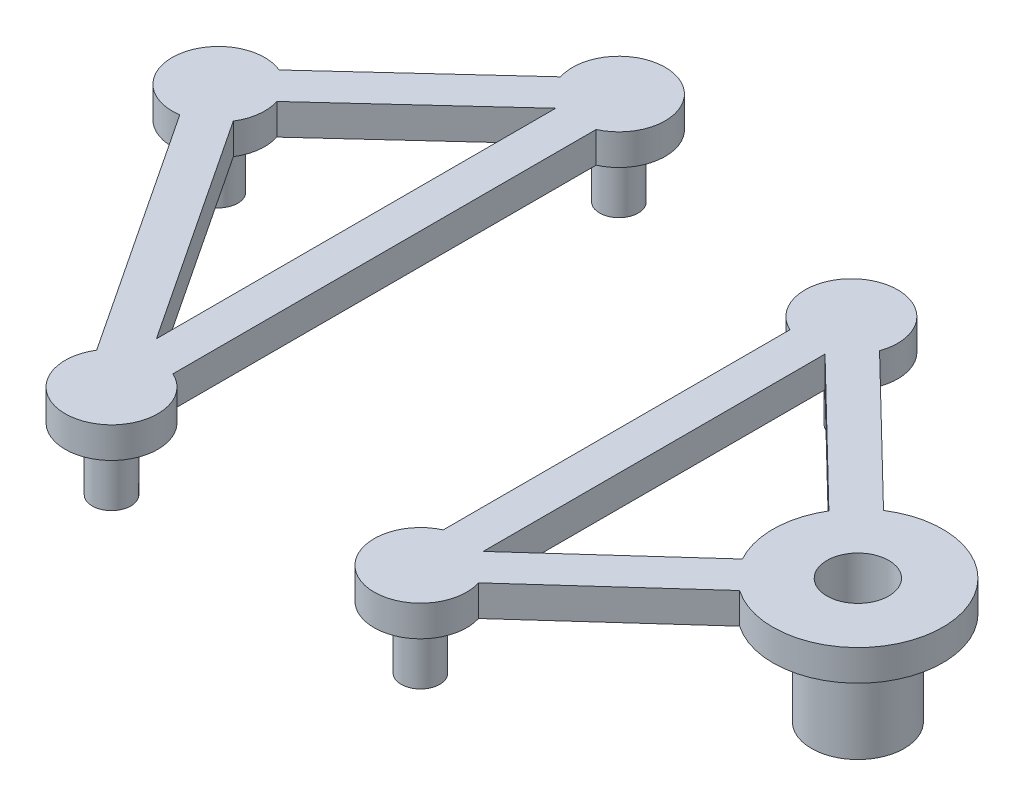
SolidWorks part; units mm, degrees
ref_plane "Спереди" through (0, 0, 0) normal (0, 0, 1) x (1, 0, 0)
ref_plane "Сверху" through (0, 0, 0) normal (0, 1, 0) x (1, 0, 0)
ref_plane "Справа" through (0, 0, 0) normal (1, 0, 0) x (0, 0, -1)
other "Configuration Table"
sketch "Эскиз1" plane through (0, 0, 0) normal (0, 1, 0) x (1, 0, 0)
  line L0 (-67.0272, 40.8721) -> (-40, 0) construction
  line L1 (-40, 0) -> (-40, 65.7) construction
  line L2 (-40, 65.7) -> (-67.0272, 40.8721) construction
  line L3 (0, 55.8) -> (29.7602, 26.8763) construction
  line L4 (29.7602, 26.8763) -> (0, 0) construction
  line L5 (0, 55.8) -> (0, 0) construction
  line L6 (0, 0) -> (-40, 0) construction
  line L8 (-66.0981, 34.9348) -> (-43.8076, 1.2257) construction
  line L11 (-48.2821, 17.0572) -> (-25.9916, -16.6519) construction
  line L12 (-37.5, 40.8721) -> (-37.5, 25.5534) construction
  line L14 (-42.5, 45.1596) -> (-42.5, 29.8408) construction
  line L15 (-58.9446, 51.6917) -> (-52.0529, 58.0226) construction
  line L17 (-54.6234, 48.8719) -> (-47.7317, 55.2027) construction
  line L18 (-64.7017, 46.4032) -> (-45.708, 63.8512)
  line L20 (-37.5, 60.2456) -> (-37.5, 5.4544)
  line L22 (-66.104, 34.9436) -> (-45.0938, 3.1707)
  line L32 (-61.3191, 42.721) -> (-42.5, 60.0087)
  line L33 (-42.5, 60.0087) -> (-42.5, 8.3131)
  line L34 (-42.5, 8.3131) -> (-61.9334, 37.7015)
  line L36 (-2.5, 38.1926) -> (-2.5, 20.958) construction
  line L38 (2.5, 19.403) -> (2.5, 2.1683) construction
  line L39 (9.5911, 49.9647) -> (19.4126, 40.4193) construction
  line L41 (9.1257, 43.4447) -> (18.1439, 34.68) construction
  line L43 (9.8251, 12.2416) -> (16.8272, 18.5652) construction
  line L45 (11.5829, 7.0919) -> (19.8959, 14.5993) construction
  line L46 (20.1346, 21.5521) -> (2.5, 5.6263)
  line L53 (2.5, 5.6263) -> (2.5, 49.8841)
  line L55 (2.5, 49.8841) -> (20.336, 32.5494)
  line L57 (-2.5, 50.3456) -> (-2.5, 5.4544)
  line L58 (5.7235, 1.8003) -> (23.4858, 17.8413)
  line L59 (5.6538, 53.7913) -> (23.8208, 36.135)
  circle A14 centre (-40, 65.7) radius 6 construction
  circle A15 centre (-67.0272, 40.8721) radius 6 construction
  circle A16 centre (-40, 0) radius 6 construction
  circle A17 centre (0, 0) radius 6 construction
  circle A18 centre (29.7602, 26.8763) radius 11 construction
  circle A19 centre (0, 55.8) radius 6 construction
  arc A20 (-66.104, 34.9436) -> (-64.7017, 46.4032) centre (-67.0272, 40.8721) cw
  arc A21 (-45.708, 63.8512) -> (-37.5, 60.2456) centre (-40, 65.7) cw
  arc A22 (-45.0938, 3.1707) -> (-37.5, 5.4544) centre (-40, 0) ccw
  arc A23 (-61.3191, 42.721) -> (-61.9334, 37.7015) centre (-67.0272, 40.8721) cw
  arc A24 (5.6538, 53.7913) -> (-2.5, 50.3456) centre (0, 55.8) ccw
  arc A25 (23.4858, 17.8413) -> (23.8208, 36.135) centre (29.7602, 26.8763) ccw
  arc A26 (-2.5, 5.4544) -> (5.7235, 1.8003) centre (0, 0) ccw
  arc A27 (20.336, 32.5494) -> (20.1346, 21.5521) centre (29.7602, 26.8763) ccw
  dimension "D14" = 12
  dimension "D15" = 12
  dimension "D16" = 12
  dimension "D17" = 12
  dimension "D18" = 12
  dimension "D19" = 22
  dimension "D1" = 55.8
  dimension "D2" = 40.1
  dimension "D3" = 41.5
  dimension "D4" = 65.7
  dimension "D5" = 49
  dimension "D6" = 36.7
  dimension "D7" = 40
  dimension "D8" = 2.5
  dimension "D9" = 2.5
  dimension "D10" = 2.5
  dimension "D11" = 2.5
  dimension "D12" = 2.5
  dimension "D13" = 2.5
  dimension "D20" = 2.5
  dimension "D21" = 2.5
  dimension "D22" = 2.5
  dimension "D23" = 2.5
  dimension "D24" = 2.5
  dimension "D25" = 2.5
extrude "Бобышка-Вытянуть1" add sketch "Эскиз1" along normal blind 4
sketch "Эскиз2" plane through (0, 0, 0) normal (0, -1, 0) x (1, 0, 0)
  circle A1 centre (-40, 0) radius 2.5
  circle A3 centre (-40, -65.7) radius 2.5
  circle A5 centre (-67.0272, -40.8721) radius 2.5
  dimension "D1" = 5
  dimension "D2" = 5
  dimension "D3" = 5
extrude "Бобышка-Вытянуть2" add sketch "Эскиз2" along normal blind 8.1
sketch "Эскиз3" plane through (0, 0, 0) normal (0, -1, 0) x (1, 0, 0)
  circle A0 centre (0, 0) radius 2.5
  circle A1 centre (0, -55.8) radius 2.5
  dimension "D1" = 5
  dimension "D2" = 5
extrude "Бобышка-Вытянуть3" add sketch "Эскиз3" along normal blind 8.1
sketch "Эскиз4" plane through (0, 0, 0) normal (0, -1, 0) x (1, 0, 0)
  circle A0 centre (29.7602, -26.8763) radius 6
  dimension "D1" = 12
extrude "Бобышка-Вытянуть4" add sketch "Эскиз4" along normal blind 12.1
sketch "Эскиз5" plane through (0, 4, 0) normal (0, 1, 0) x (1, 0, 0)
  circle A0 centre (29.7602, 26.8763) radius 4
  dimension "D1" = 8
extrude "Вырез-Вытянуть1" cut sketch "Эскиз5" against normal through all
equation "\"A\"= 12мм"
equation "\"B\"= 22мм"
equation "\"w\"= 5мм"
equation "\"D8@Эскиз1\"=\"w\"/2"
equation "\"D9@Эскиз1\"=\"w\"/2"
equation "\"D10@Эскиз1\"=\"w\"/2"
equation "\"D11@Эскиз1\"=\"w\"/2"
equation "\"D12@Эскиз1\"=\"w\"/2"
equation "\"D13@Эскиз1\"=\"w\"/2"
equation "\"D14@Эскиз1\"=\"A\""
equation "\"D15@Эскиз1\"=\"A\""
equation "\"D16@Эскиз1\"=\"A\""
equation "\"D17@Эскиз1\"=\"A\""
equation "\"D18@Эскиз1\"=\"A\""
equation "\"D19@Эскиз1\"=\"B\""
equation "\"D20@Эскиз1\"=\"w\"/2"
equation "\"D21@Эскиз1\"=\"w\"/2"
equation "\"D22@Эскиз1\"=\"w\"/2"
equation "\"D23@Эскиз1\"=\"w\"/2"
equation "\"D24@Эскиз1\"=\"w\"/2"
equation "\"D25@Эскиз1\"=\"w\"/2"
equation "\"innd\"= 5мм"
equation "\"extd\"= 8мм"
equation "\"D1@Эскиз2\"=\"innd\""
equation "\"D2@Эскиз2\"=\"innd\""
equation "\"D3@Эскиз2\"=\"innd\""
equation "\"D1@Эскиз3\"=\"innd\""
equation "\"D2@Эскиз3\"=\"innd\""
